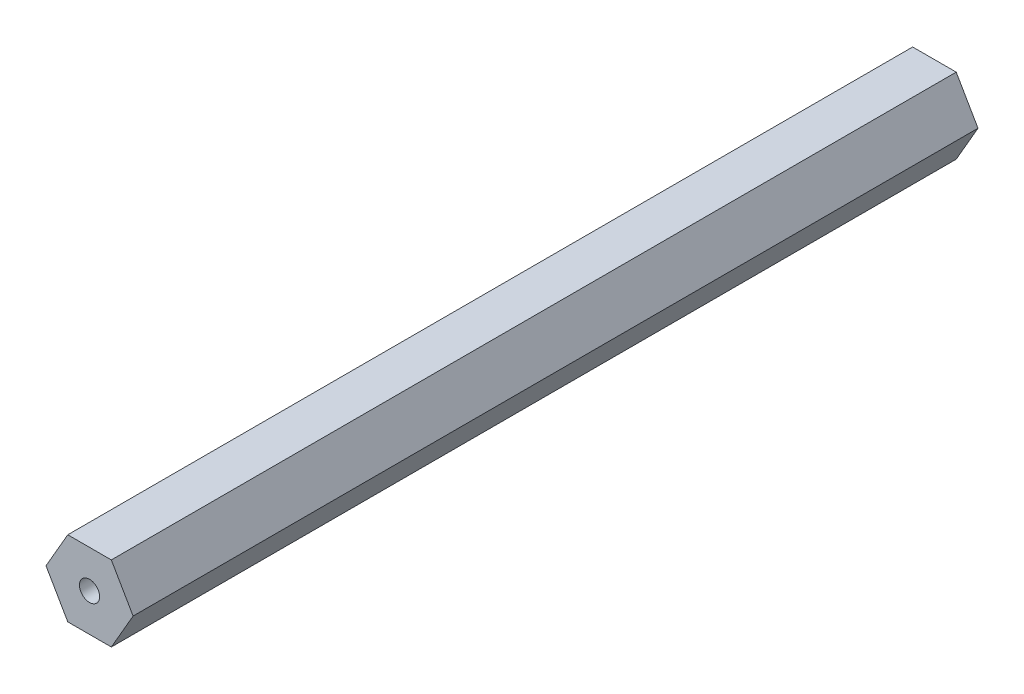
SolidWorks part; units mm, degrees
ref_plane "Front Plane" through (0, 0, 0) normal (0, 0, 1) x (1, 0, 0)
ref_plane "Top Plane" through (0, 0, 0) normal (0, 1, 0) x (1, 0, 0)
ref_plane "Right Plane" through (0, 0, 0) normal (1, 0, 0) x (0, 0, -1)
sketch "Sketch1" plane through (0, 0, 0) normal (0, 0, 1) x (1, 0, 0)
  line L1 (16.408, -2.6676) -> (13.6584, 2.0949)
  line L2 (13.6584, 2.0949) -> (8.1591, 2.0949)
  line L3 (8.1591, 2.0949) -> (5.4095, -2.6676)
  line L4 (5.4095, -2.6676) -> (8.1591, -7.4301)
  line L5 (8.1591, -7.4301) -> (13.6584, -7.4301)
  line L6 (13.6584, -7.4301) -> (16.408, -2.6676)
  circle A0 centre (10.9088, -2.6676) radius 4.7625 construction
  circle A1 centre (10.9088, -2.6676) radius 1.27
  dimension "D1" = 9.525
extrude "Boss-Extrude1" add sketch "Sketch1" along normal blind 106.68
